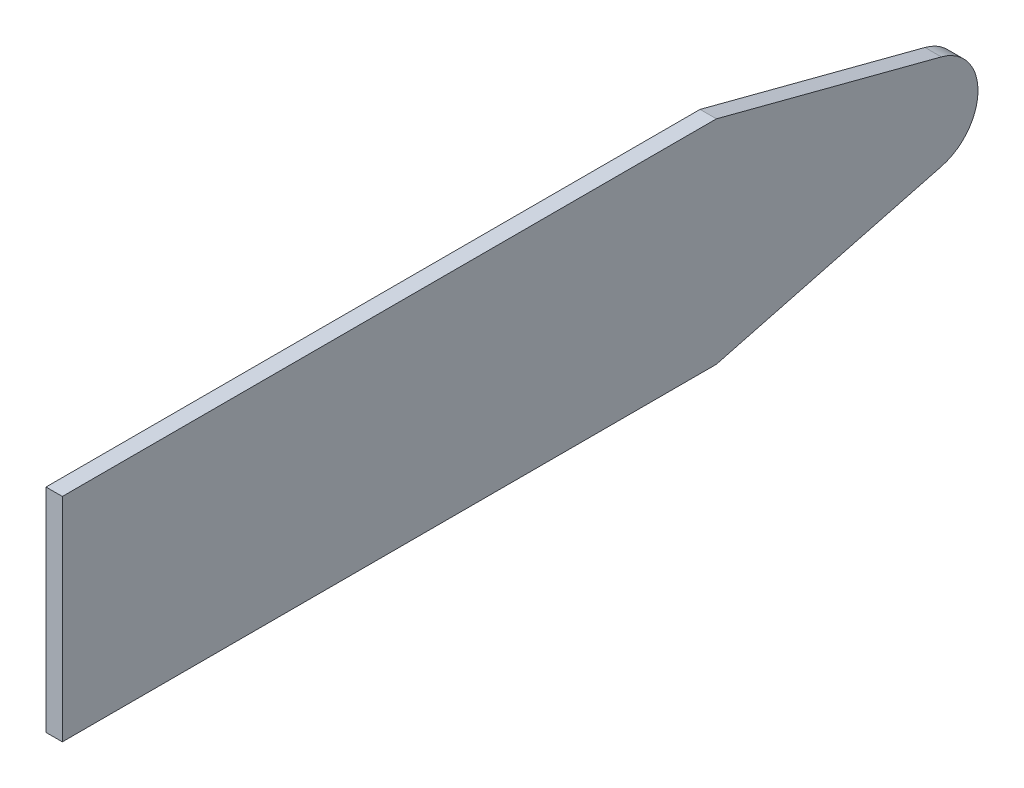
SolidWorks part; units mm, degrees
material "Q355"
ref_plane "前视基准面" through (0, 0, 0) normal (0, 0, 1) x (1, 0, 0)
ref_plane "上视基准面" through (0, 0, 0) normal (0, 1, 0) x (1, 0, 0)
ref_plane "右视基准面" through (0, 0, 0) normal (1, 0, 0) x (0, 0, -1)
sketch "草图1" plane through (0, 0, 0) normal (1, 0, 0) x (0, 0, -1)
  line L0 (7.589, 29.0242) -> (-130, 65)
  line L1 (-130, 65) -> (-530, 65)
  line L2 (-530, 65) -> (-530, -65)
  line L3 (-530, -65) -> (-130, -65)
  line L4 (-130, -65) -> (7.589, -29.0242)
  arc A0 (7.589, -29.0242) -> (7.589, 29.0242) centre (0, 0) ccw
  dimension "D1" = 30
  dimension "D2" = 130
  dimension "D3" = 65
  dimension "D4" = 530
  dimension "D5" = 400
extrude "凸台-拉伸1" add sketch "草图1" along normal blind 10
